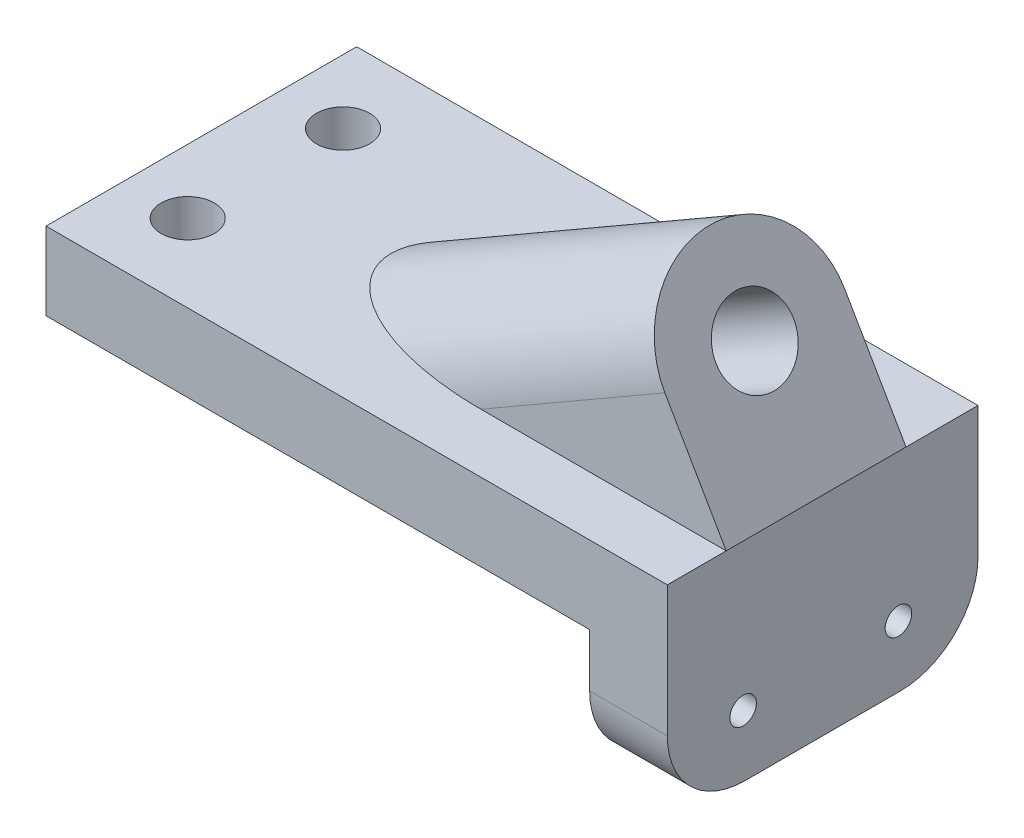
SolidWorks part; units mm, degrees
ref_plane "정면" through (0, 0, 0) normal (0, 0, 1) x (1, 0, 0)
ref_plane "윗면" through (0, 0, 0) normal (0, 1, 0) x (1, 0, 0)
ref_plane "우측면" through (0, 0, 0) normal (1, 0, 0) x (0, 0, -1)
sketch "스케치1" plane through (0, 0, 0) normal (0, 0, 1) x (1, 0, 0)
  line L0 (0, 0) -> (152, 0)
  line L1 (152, 0) -> (152, -51)
  line L2 (152, -51) -> (133, -51)
  line L3 (133, -51) -> (133, -19)
  line L4 (133, -19) -> (0, -19)
  line L5 (0, -19) -> (0, 0)
  dimension "D1" = 152
  dimension "D2" = 19
  dimension "D3" = 51
  dimension "D4" = 19
extrude "보스-돌출1" add sketch "스케치1" along normal blind 76 contours L0 L1 L2 L3 L4 L5
ref_plane "평면1" through (114, 65.8179, 0) normal (0.866, 0.5, 0) x (0, 0, -1)
sketch "스케치2" plane through (114, 65.8179, 0) normal (0.866, 0.5, 0) x (0, 0, -1)
  line L0 (-76, -76) -> (0, -76) construction
  line L1 (-61.6044, -46) -> (-61.6044, -76)
  line L2 (-17.6044, -46) -> (-17.6044, -76)
  line L3 (-61.6044, -76) -> (-17.6044, -76)
  arc A0 (-17.6044, -46) -> (-61.6044, -46) centre (-39.6044, -46) ccw
  circle A1 centre (-39.6044, -46) radius 9.5
  dimension "D1" = 30
  dimension "D2" = 44
  dimension "D3" = 19
extrude "보스-돌출2" add sketch "스케치2" against normal up to surface (68.416 mm away) contours L1 L3 L2 A0
sketch "스케치3" plane through (152, 0, 0) normal (1, 0, 0) x (0, 0, -1)
  circle A0 centre (-57.459, -35.9136) radius 3.25
  circle A1 centre (-19.459, -35.9136) radius 3.25
  dimension "D1" = 6.5
  dimension "D2" = 6.5
  dimension "D3" = 38
extrude "컷-돌출1" cut sketch "스케치3" against normal blind 76 contours A0 | A1
sketch "스케치4" plane through (0, 0, 0) normal (0, 1, 0) x (1, 0, 0)
  line L0 (0, -76) -> (152, -76) construction
  circle A0 centre (15.6653, -57) radius 6.5
  circle A1 centre (15.6653, -19) radius 6.5
  dimension "D2" = 13
  dimension "D3" = 13
  dimension "D1" = 38
  dimension "D4" = 19
extrude "컷-돌출2" cut sketch "스케치4" against normal blind 76 contours A0 | A1
fillet "필렛2" radius 19 2 edges at (142.5, -51, 0) (142.5, -51, 76)
